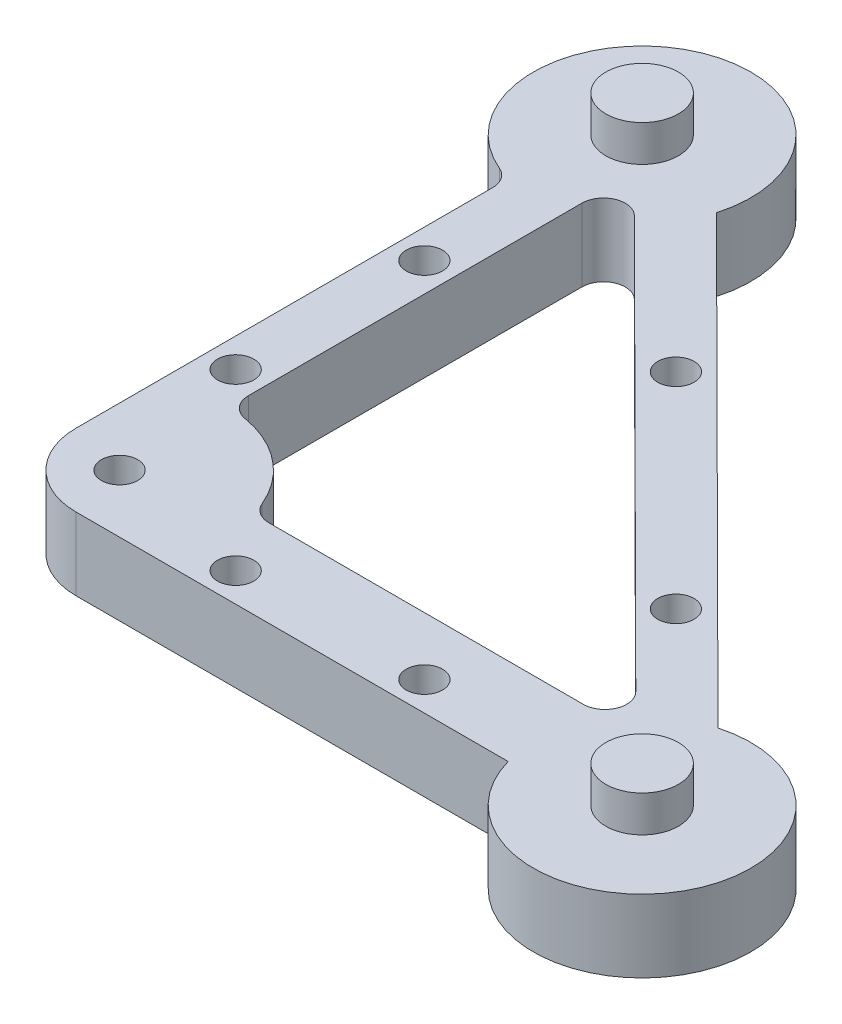
SolidWorks part; units mm, degrees
ref_plane "Front Plane" through (0, 0, 0) normal (0, 0, 1) x (1, 0, 0)
ref_plane "Top Plane" through (0, 0, 0) normal (0, 1, 0) x (1, 0, 0)
ref_plane "Right Plane" through (0, 0, 0) normal (1, 0, 0) x (0, 0, -1)
sketch "Sketch1" plane through (0, 0, 0) normal (0, 1, 0) x (1, 0, 0)
  line L0 (-25.5901, 75.8342) -> (36, 14.4568)
  line L4 (-44, 65.5432) -> (-44, -4)
  line L13 (25.5432, -4) -> (-44, -4)
  arc A0 (25.5432, -4) -> (36, 14.4568) centre (40, 0) ccw
  arc A1 (-25.5901, 75.8342) -> (-44, 65.5432) centre (-40, 80) ccw
extrude "Boss-Extrude1" add sketch "Sketch1" along normal blind 10 contours L4 L13 A0 L0 A1
sketch "Sketch2" plane through (0, 10, 0) normal (0, 1, 0) x (1, 0, 0)
  circle A0 centre (-40, 80) radius 5
extrude "Boss-Extrude2" add sketch "Sketch2" along normal blind 5
sketch "Sketch3" plane through (0, 10, 0) normal (0, 1, 0) x (1, 0, 0)
  circle A0 centre (40, 0) radius 5
extrude "Boss-Extrude3" add sketch "Sketch3" along normal blind 5
sketch "Sketch4" plane through (0, 10, 0) normal (0, 1, 0) x (1, 0, 0)
  circle A0 centre (-40, 50) radius 2.5
extrude "Cut-Extrude1" cut sketch "Sketch4" against normal through all
sketch "Sketch5" plane through (0, 10, 0) normal (0, 1, 0) x (1, 0, 0)
  circle A0 centre (-40, 24) radius 2.5
extrude "Cut-Extrude2" cut sketch "Sketch5" against normal through all
sketch "Sketch6" plane through (0, 10, 0) normal (0, 1, 0) x (1, 0, 0)
  circle A0 centre (10, 0) radius 2.5
extrude "Cut-Extrude3" cut sketch "Sketch6" against normal through all
sketch "Sketch7" plane through (0, 10, 0) normal (0, 1, 0) x (1, 0, 0)
  circle A0 centre (-16, 0) radius 2.5
extrude "Cut-Extrude4" cut sketch "Sketch7" against normal through all contours A0
sketch "Sketch8" plane through (0, 10, 0) normal (0, 1, 0) x (1, 0, 0)
  circle A0 centre (-36, 4) radius 2.5
extrude "Cut-Extrude5" cut sketch "Sketch8" against normal through all
sketch "Sketch10" plane through (0, 10, 0) normal (0, 1, 0) x (1, 0, 0)
  line L0 (-36, 74.914) -> (31.1459, 8)
  line L4 (-36, 74.914) -> (-36, 19)
  line L9 (-21.5432, 8) -> (31.1459, 8)
  arc A2 (-21.5432, 8) -> (-36, 19) centre (-36, 4) ccw
extrude "Cut-Extrude6" cut sketch "Sketch10" against normal through all
fillet "Fillet3" radius 3 1 edges at (-44, 5, -65.5432)
sketch "Sketch11" plane through (0, 10, 0) normal (0, 1, 0) x (1, 0, 0)
  circle A0 centre (-9.3981, 54.0511) radius 2.5
extrude "Cut-Extrude7" cut sketch "Sketch11" against normal through all
sketch "Sketch12" plane through (0, 10, 0) normal (0, 1, 0) x (1, 0, 0)
  circle A0 centre (18.8861, 25.7669) radius 2.5
extrude "Cut-Extrude8" cut sketch "Sketch12" against normal through all
fillet "Fillet4" radius 3 1 edges at (-36, 5, -74.914)
fillet "Fillet5" radius 3 1 edges at (31.1459, 5, -8)
fillet "Fillet6" radius 3 1 edges at (-36, 5, -19)
fillet "Fillet7" radius 3 1 edges at (-21.5432, 5, -8)
fillet "Fillet8" radius 10 1 edges at (-44, 5, 4)
